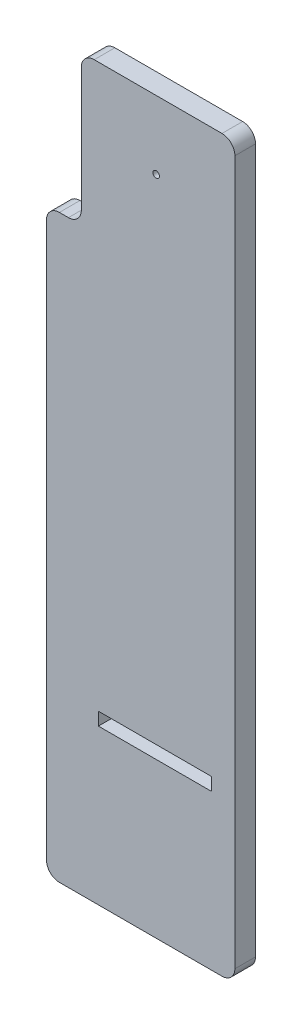
SolidWorks part; units mm, degrees
ref_plane "前视基准面" through (0, 0, 0) normal (0, 0, 1) x (1, 0, 0)
ref_plane "上视基准面" through (0, 0, 0) normal (0, 1, 0) x (1, 0, 0)
ref_plane "右视基准面" through (0, 0, 0) normal (1, 0, 0) x (0, 0, -1)
other "Configuration Table"
sketch "草图2" plane through (0, 0, 0) normal (0, 0, 1) x (1, 0, 0)
  line L1 (6.45, -13.03) -> (6.45, -25.9304) construction
  line L2 (6.45, -15.08) -> (6.45, -10.98) construction
  line L3 (8.15, -22.48) -> (-8.15, -22.48) construction
  line L4 (6.45, -22.48) -> (-8.15, -22.48)
  line L5 (6.45, -22.48) -> (6.45, 34.08)
  line L6 (6.45, 34.08) -> (-8.15, 34.08)
  line L7 (-8.15, -22.48) -> (-8.15, 34.08)
  line L8 (-0.724, 33.08) -> (1.424, 33.08) construction
  line L9 (-8.15, -22.48) -> (-8.15, 22.48) construction
  line L11 (4.625, -10.48) -> (-4.125, -10.48)
  line L12 (4.625, -10.48) -> (4.625, -9.48)
  line L13 (4.625, -9.48) -> (-4.125, -9.48)
  line L14 (-4.125, -10.48) -> (-4.125, -9.48)
  line L15 (-4.125, -10.48) -> (-5.45, -10.48) construction
  line L16 (-4.125, -10.48) -> (-4.125, -12.48) construction
  line L17 (4.625, -12.48) -> (4.625, -10.48) construction
  circle A0 centre (0.35, 28.78) radius 0.25 construction
  circle A1 centre (0.35, 28.78) radius 0.25
  point P22 (0, 0)
  point P23 (0, 0)
  point P24 (0, 0)
  point P25 (0, 0)
  dimension "D1" = 1
  dimension "D2" = 1
extrude "凸台-拉伸1" add sketch "草图2" along normal blind 1.6
sketch "草图3" plane through (0, 0, 0) normal (0, 0, -1) x (-1, 0, 0)
  line L0 (-6.45, 34.08) -> (8.15, 34.08) construction
  line L1 (5.45, 34.08) -> (8.15, 34.08)
  line L2 (5.45, 34.08) -> (5.45, 22.48)
  line L3 (5.45, 22.48) -> (8.15, 22.48)
  line L4 (8.15, 34.08) -> (8.15, 22.48)
  line L5 (8.15, 34.08) -> (8.15, -22.48) construction
  line L6 (8.15, 22.48) -> (-8.15, 22.48) construction
  line L7 (3.95, 27.706) -> (3.95, 29.854) construction
  dimension "D1" = 1.5
extrude "切除-拉伸1" cut sketch "草图3" against normal blind 1.6
fillet "圆角2" radius 1 6 edges at (6.45, -22.48, 0.8) (-8.15, -22.48, 0.8) (-8.15, 22.48, 0.8) (6.45, 34.08, 0.8) (-5.45, 34.08, 0.8) (-5.45, 22.48, 0.8)
